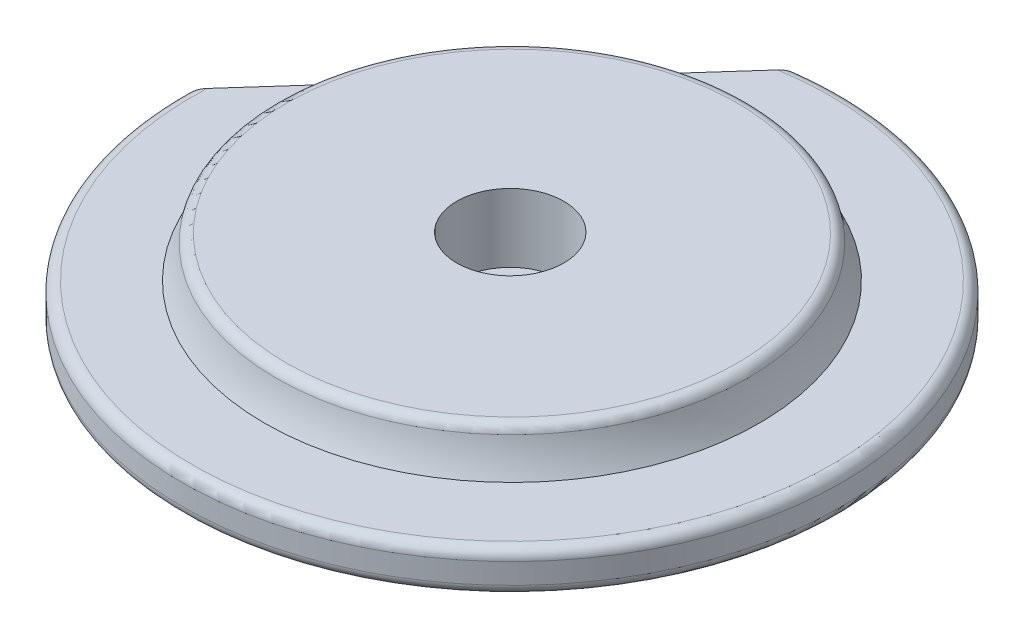
SolidWorks part; units mm, degrees
ref_plane "Plan de face" through (0, 0, 0) normal (0, 0, 1) x (1, 0, 0)
ref_plane "Plan de dessus" through (0, 0, 0) normal (0, 1, 0) x (1, 0, 0)
ref_plane "Plan de droite" through (0, 0, 0) normal (1, 0, 0) x (0, 0, -1)
sketch "Esquisse1" plane through (0, 0, 0) normal (0, 0, 1) x (1, 0, 0)
  line L0 (0, 0) -> (80, 0)
  line L1 (23.2031, 20) -> (80, 20)
  line L2 (0, 0) -> (0, 10)
  line L3 (0, 10) -> (20, 10)
  line L4 (80, 20) -> (80, 0)
  arc A1 (20, 10) -> (23.2031, 20) centre (-7.0047, 24.1629) ccw
  dimension "D1" = 20
  dimension "D2" = 10
  dimension "D3" = 20
  dimension "D4" = 80
revolve "Révolution1" add sketch "Esquisse1" angle 360 about L4
fillet "Congé1" radius 2.5 3 edges at (80, 20, 56.7969) (80, 0, 80) (80, 10, 80)
sketch "Esquisse3" plane through (0, 10, 0) normal (0, 1, 0) x (1, 0, 0)
  line L0 (0.0017, 0.5216) -> (70.5177, 79.436)
  arc A0 (0.0017, 0.5216) -> (70.5177, 79.436) centre (80, 0) cw
  circle A1 centre (80, 0) radius 80 construction
extrude "Enlèv. mat.-Extru.1" cut sketch "Esquisse3" against normal up to next
hole_wizard "Chambrage pour vis à tête hexagonale M161" positions "Esquisse5" profile "Esquisse6" counterbore size "M16" standard "DIN"
sketch "Esquisse5" plane through (0, 20, 0) normal (0, 1, 0) x (1, 0, 0)
  point P0 (79.5911, 0)
sketch "Esquisse6" plane through (79.5911, 20, 0) normal (1, 0, 0) x (0, 0, 1)
  line L0 (0, 0) -> (0, 25.2575)
  line L1 (0, 25.2575) -> (8.75, 20)
  line L2 (8.75, 20) -> (8.75, 16.6)
  line L3 (8.75, 16.6) -> (13, 16.6)
  line L4 (13, 16.6) -> (13, 0)
  line L5 (13, 0) -> (0, 0)
  line L10 (0, 25.2575) -> (-8.75, 20) construction
  line L11 (0, -6.35) -> (0, 107.95) construction
  dimension "Diamètre du perçage" = 17.5
  dimension "Profondeur du perçage" = 20
  dimension "Diamètre du chambrage" = 26
  dimension "Profondeur du chambrage" = 16.6
  dimension "Angle de pointe" = 118
scale "Echelle1" scale about centroid uniform scaling yes scale factor 0.25
